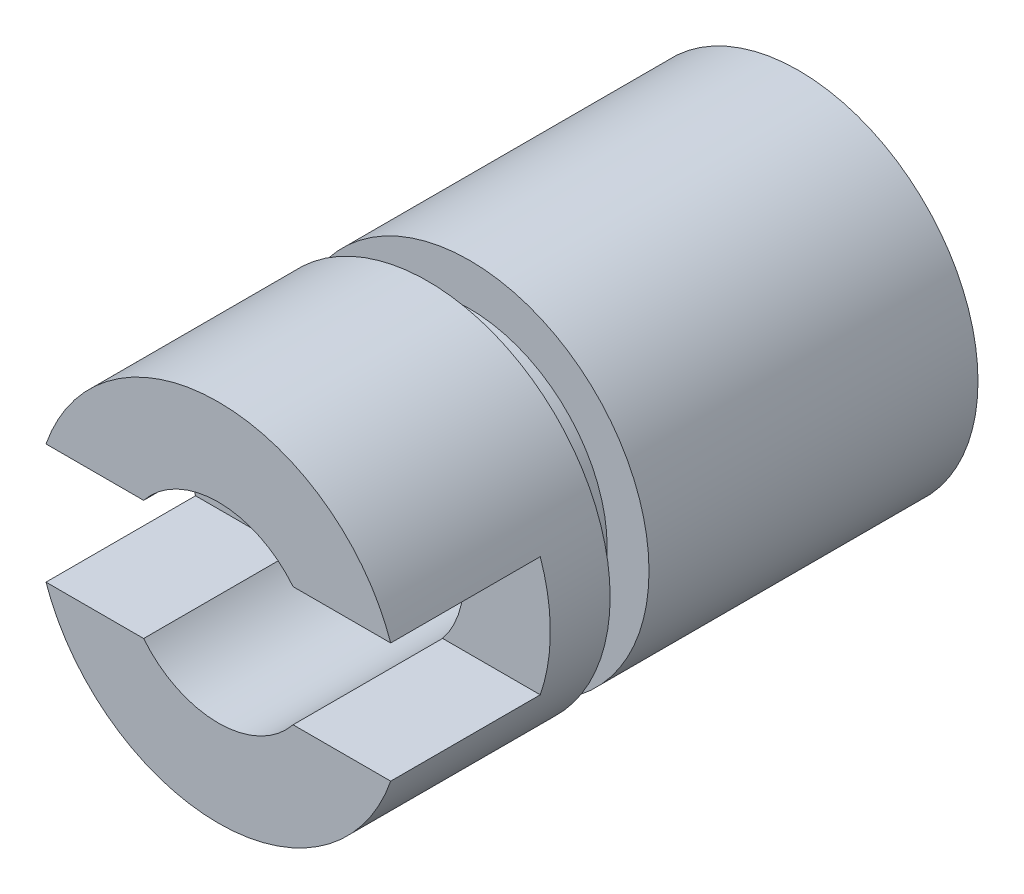
SolidWorks part; units mm, degrees
ref_plane "Front Plane" through (0, 0, 0) normal (0, 0, 1) x (1, 0, 0)
ref_plane "Top Plane" through (0, 0, 0) normal (0, 1, 0) x (1, 0, 0)
ref_plane "Right Plane" through (0, 0, 0) normal (1, 0, 0) x (0, 0, -1)
sketch "Sketch1" plane through (0, 0, 0) normal (0, 0, 1) x (1, 0, 0)
  circle A0 centre (0, 0) radius 3
  circle A1 centre (0, 0) radius 1.6
  dimension "D1" = 6
  dimension "D2" = 3.2
extrude "Boss-Extrude1" add sketch "Sketch1" along normal blind 5.5
sketch "Sketch2" plane through (0, 0, 5.5) normal (0, 0, 1) x (1, 0, 0)
  circle A0 centre (0, 0) radius 1.6
  circle A1 centre (0, 0) radius 2.3
  circle A2 centre (0, 0) radius 3 construction
  dimension "D1" = 0.7
extrude "Boss-Extrude2" add sketch "Sketch2" along normal blind 0.7 contours A1 | A0
sketch "Sketch3" plane through (0, 0, 6.2) normal (0, 0, 1) x (1, 0, 0)
  circle A0 centre (0, 0) radius 1.6
  circle A1 centre (0, 0) radius 3.05
  circle M1 centre (0, 0) radius 2.3
  circle M2 centre (0, 0) radius 1.6
  dimension "D1" = 6.1
extrude "Boss-Extrude3" add sketch "Sketch3" along normal blind 3.5 contours A1 M1 | M1 M2
sketch "Sketch4" plane through (0, 0, 9.7) normal (0, 0, 1) x (1, 0, 0)
  line L1 (3.1, -1) -> (-3.1, -1)
  line L2 (3.1, -1) -> (3.1, 1)
  line L3 (3.1, 1) -> (-3.1, 1)
  line L4 (-3.1, -1) -> (-3.1, 1)
  line L5 (3.1, -1) -> (-3.1, 1) construction
  line L6 (3.1, 1) -> (-3.1, -1) construction
  point P0 (0, 0)
  dimension "D1" = 2
  dimension "D2" = 6.2
extrude "Cut-Extrude1" cut sketch "Sketch4" against normal blind 2.5
